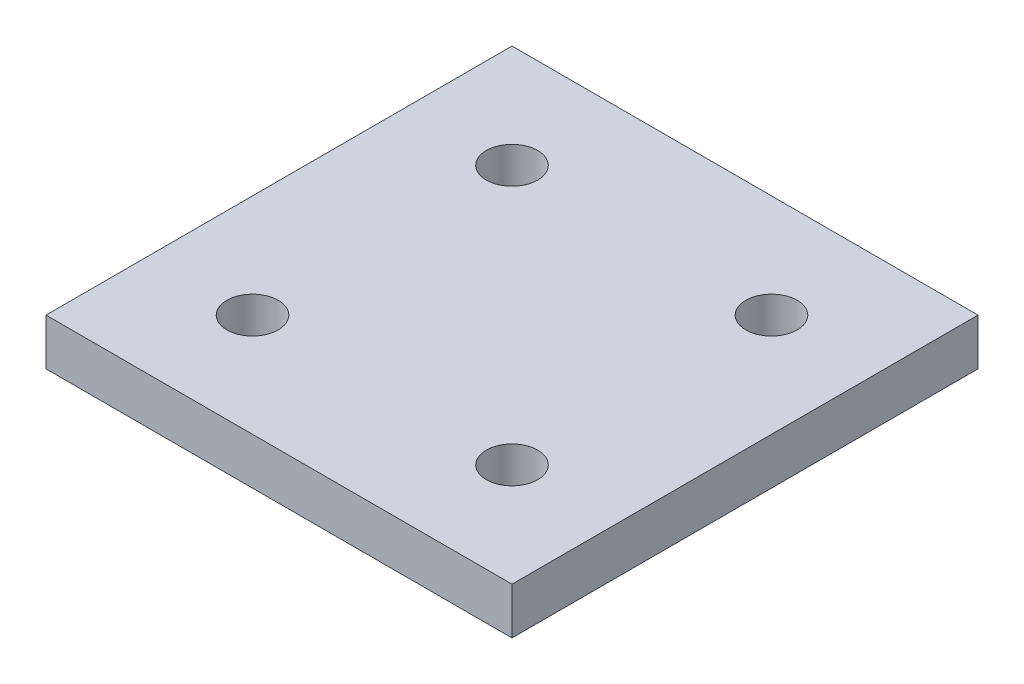
SolidWorks part; units mm, degrees
ref_plane "Front Plane" through (0, 0, 0) normal (0, 0, 1) x (1, 0, 0)
ref_plane "Top Plane" through (0, 0, 0) normal (0, 1, 0) x (1, 0, 0)
ref_plane "Right Plane" through (0, 0, 0) normal (1, 0, 0) x (0, 0, -1)
sketch "Sketch1" plane through (0, 0, 0) normal (0, 1, 0) x (1, 0, 0)
  line L1 (-31.75, 31.75) -> (31.75, 31.75)
  line L2 (-31.75, 31.75) -> (-31.75, -31.75)
  line L3 (-31.75, -31.75) -> (31.75, -31.75)
  line L4 (31.75, 31.75) -> (31.75, -31.75)
  line L5 (-31.75, 31.75) -> (31.75, -31.75) construction
  line L6 (-31.75, -31.75) -> (31.75, 31.75) construction
  point P0 (0, 0)
  dimension "D1" = 63.5
extrude "Boss-Extrude1" add sketch "Sketch1" along normal blind 6.35
sketch "Sketch2" plane through (0, 6.35, 0) normal (0, 1, 0) x (1, 0, 0)
  line L1 (-17.68, 17.68) -> (17.68, 17.68) construction
  line L2 (-17.68, 17.68) -> (-17.68, -17.68) construction
  line L3 (-17.68, -17.68) -> (17.68, -17.68) construction
  line L4 (17.68, 17.68) -> (17.68, -17.68) construction
  line L5 (-17.68, 17.68) -> (17.68, -17.68) construction
  line L6 (-17.68, -17.68) -> (17.68, 17.68) construction
  circle A0 centre (-17.68, 17.68) radius 3.5
  circle A1 centre (17.68, 17.68) radius 3.5
  circle A2 centre (17.68, -17.68) radius 3.5
  circle A3 centre (-17.68, -17.68) radius 3.5
  point P0 (-23.5758, -23.9226)
  point P8 (0, 0)
  point P14 (-23.2453, 23.5758)
  dimension "D1" = 7
  dimension "D2" = 35.36
extrude "Cut-Extrude1" cut sketch "Sketch2" against normal up to surface (6.35 mm away) up to face at (0, 0, 0)
